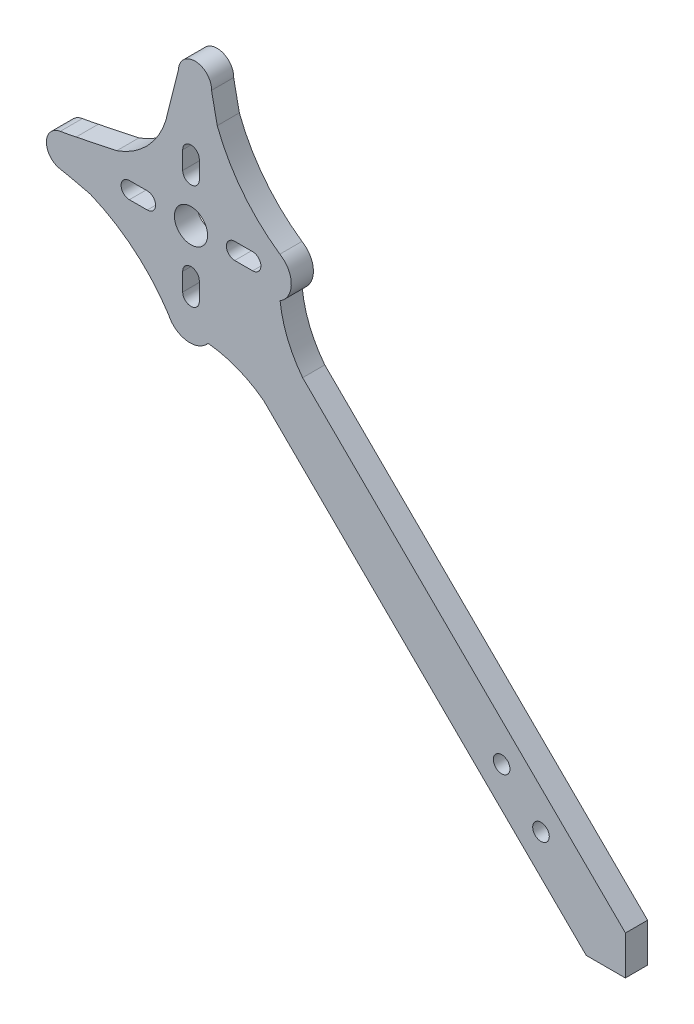
SolidWorks part; units mm, degrees
ref_plane "Front Plane" through (0, 0, 0) normal (0, 0, 1) x (1, 0, 0)
ref_plane "Top Plane" through (0, 0, 0) normal (0, 1, 0) x (1, 0, 0)
ref_plane "Right Plane" through (0, 0, 0) normal (1, 0, 0) x (0, 0, -1)
sketch "Sketch1" plane through (0, 0, 0) normal (0, 0, 1) x (1, 0, 0)
  line L0 (-180.5247, 132.1145) -> (-180.5247, 135.3488) construction
  line L5 (-182.0245, 132.1145) -> (-182.0245, 135.3488)
  line L6 (-179.0249, 132.1145) -> (-179.0249, 135.3488)
  line L11 (-180.5247, 116.3145) -> (-180.5247, 113.0801) construction
  line L12 (-182.0245, 116.3145) -> (-182.0245, 113.0801)
  line L13 (-179.0249, 116.3145) -> (-179.0249, 113.0801)
  line L18 (-172.6248, 124.2144) -> (-169.3904, 124.2144) construction
  line L19 (-172.6248, 125.7142) -> (-169.3904, 125.7142)
  line L24 (-172.6248, 122.7146) -> (-169.3904, 122.7146)
  line L27 (-188.4248, 124.2145) -> (-191.6591, 124.2145) construction
  line L30 (-188.4248, 125.7143) -> (-191.6591, 125.7144)
  line L33 (-188.4248, 122.7147) -> (-191.6591, 122.7147)
  line L34 (-200.9828, 120.5784) -> (-198.6863, 120.0325)
  line L41 (-176.8122, 147.2452) -> (-175.7843, 142.2382)
  line L42 (-201.2865, 127.7092) -> (-193.9444, 129.2401)
  line L52 (-184.6493, 140.1596) -> (-182.8093, 147.4304)
  line L59 (-167.3704, 103.3877) -> (-109.0957, 45.7145)
  line L60 (-160.3454, 110.5046) -> (-102.007, 52.7676)
  line L66 (-109.0957, 45.7145) -> (-102.0248, 45.7145)
  line L69 (-102.0248, 45.7145) -> (-102.007, 52.7676)
  circle A94 centre (-117.2748, 60.9645) radius 1.5
  arc A95 (-182.0245, 132.1145) -> (-179.0249, 132.1145) centre (-180.5247, 132.1145) ccw
  arc A96 (-179.0249, 135.3488) -> (-182.0245, 135.3488) centre (-180.5247, 135.3488) ccw
  arc A97 (-182.0245, 116.3145) -> (-179.0249, 116.3145) centre (-180.5247, 116.3145) cw
  arc A98 (-179.0249, 113.0801) -> (-182.0245, 113.0801) centre (-180.5247, 113.0801) cw
  circle A99 centre (-180.5248, 124.2145) radius 3
  arc A100 (-172.6248, 125.7142) -> (-172.6248, 122.7146) centre (-172.6248, 124.2144) ccw
  arc A101 (-169.3904, 122.7146) -> (-169.3904, 125.7142) centre (-169.3904, 124.2144) ccw
  arc A102 (-188.4248, 125.7143) -> (-188.4248, 122.7147) centre (-188.4248, 124.2145) cw
  arc A103 (-191.6591, 122.7147) -> (-191.6591, 125.7144) centre (-191.6591, 124.2145) cw
  arc A104 (-184.5844, 108.2735) -> (-177.4391, 107.3366) centre (-180.7205, 110.0259) ccw
  arc A105 (-164.4661, 127.7801) -> (-164.4248, 120.5211) centre (-166.6423, 124.1381) cw
  arc A106 (-198.6863, 120.0325) -> (-184.5844, 108.2735) centre (-210.5902, 91.4216) cw
  arc A107 (-175.7843, 142.2382) -> (-164.4661, 127.7801) centre (-146.8195, 153.2533) ccw
  arc A108 (-204.2144, 121.2664) -> (-204.1488, 127.1743) centre (-203.6591, 124.2145) cw
  arc A109 (-176.8122, 147.2452) -> (-182.8093, 147.4304) centre (-179.8108, 147.3378) ccw
  arc A110 (-204.2144, 121.2664) -> (-200.9828, 120.5784) centre (-217.1702, 52.4758) cw
  arc A111 (-204.1488, 127.1743) -> (-201.2865, 127.7092) centre (-215.5745, 196.2355) ccw
  arc A112 (-193.9444, 129.2401) -> (-184.6493, 140.1596) centre (-198.6115, 142.6288) ccw
  arc A113 (-177.4391, 107.3366) -> (-167.3704, 103.3877) centre (-179.394, 87.5411) cw
  arc A114 (-164.4248, 120.5211) -> (-160.3454, 110.5046) centre (-144.6563, 122.7331) ccw
  circle A115 centre (-124.3824, 67.9988) radius 1.5
  point P3 (-180.5247, 133.7316)
  point P12 (-180.5247, 114.6973)
  point P20 (-171.0076, 124.2144)
  point P27 (-190.0419, 124.2145)
extrude "Boss-Extrude3" add sketch "Sketch1" along normal blind 4
